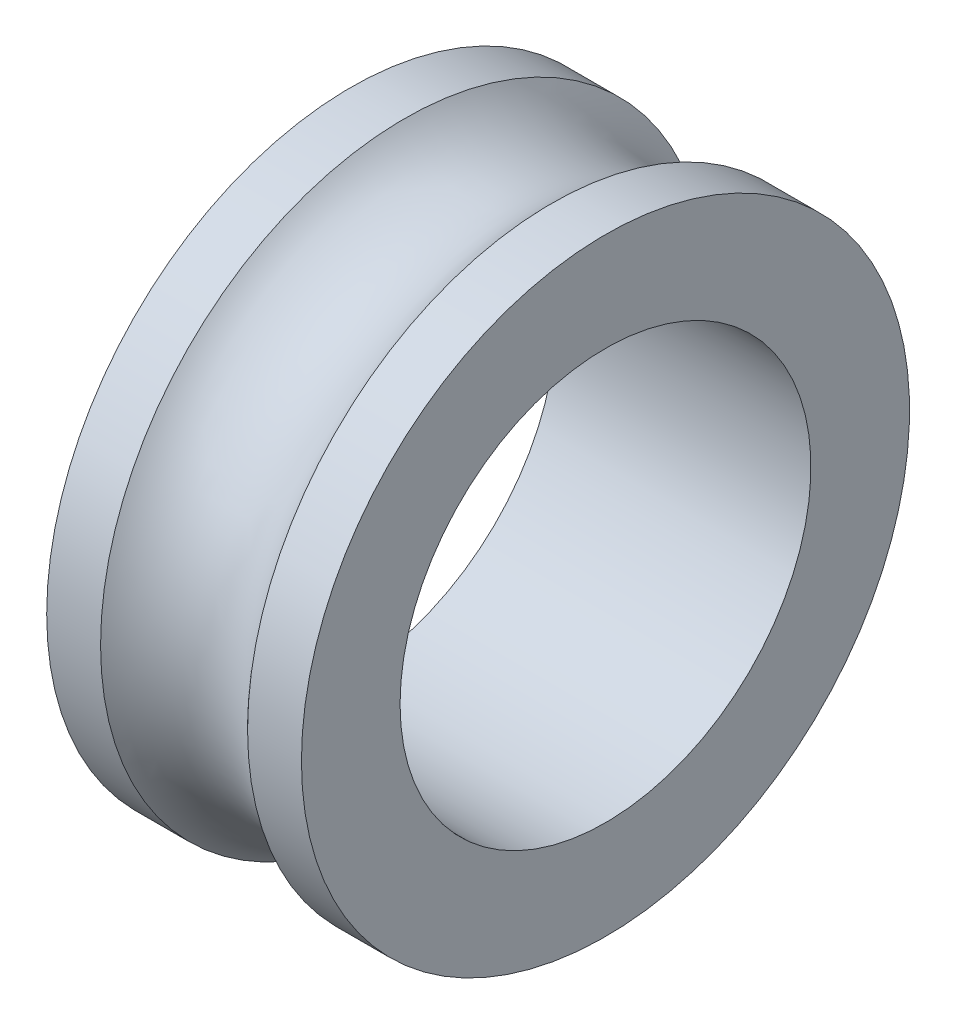
SolidWorks part; units mm, degrees
ref_plane "Front Plane" through (0, 0, 0) normal (0, 0, 1) x (1, 0, 0)
ref_plane "Top Plane" through (0, 0, 0) normal (0, 1, 0) x (1, 0, 0)
ref_plane "Right Plane" through (0, 0, 0) normal (1, 0, 0) x (0, 0, -1)
sketch "Sketch2" plane through (0, 0, 0) normal (0, 0, 1) x (1, 0, 0)
  line L0 (-31.1856, -18.9207) -> (32.2994, -18.9207) construction
  line L1 (-6.5557, 18.0793) -> (0, 18.0793)
  line L2 (-31, 18.0793) -> (-24.4443, 18.0793)
  line L3 (-31, 18.0793) -> (-31, 6.0793)
  line L4 (-31, 6.0793) -> (0, 6.0793)
  line L5 (0, 18.0793) -> (0, 6.0793)
  line L6 (-31, 18.0793) -> (0, 6.0793) construction
  line L7 (-31, 6.0793) -> (0, 18.0793) construction
  arc A0 (-24.4443, 18.0793) -> (-6.5557, 18.0793) centre (-15.5, 26.0793) ccw
  point P2 (-15.5, 12.0793)
  dimension "D4" = 12
  dimension "D1" = 31
  dimension "D2" = 25
  dimension "D3" = 37
  dimension "D5" = 8
  dimension "D6" = 0
revolve "Revolve1" add sketch "Sketch2" angle 360 about L0
